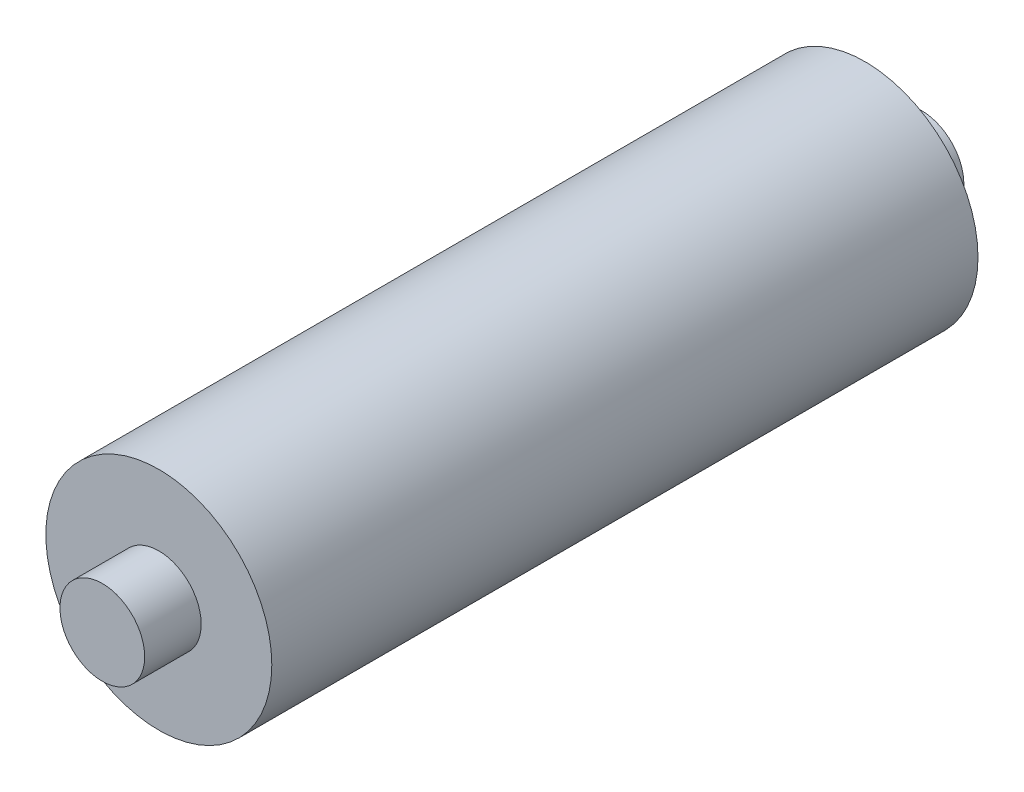
SolidWorks part; units mm, degrees
ref_plane "Front Plane" through (0, 0, 0) normal (0, 0, 1) x (1, 0, 0)
ref_plane "Top Plane" through (0, 0, 0) normal (0, 1, 0) x (1, 0, 0)
ref_plane "Right Plane" through (0, 0, 0) normal (1, 0, 0) x (0, 0, -1)
sketch "Sketch1" plane through (0, 0, 0) normal (0, 0, 1) x (1, 0, 0)
  circle A0 centre (0, 0) radius 40
  dimension "D1" = 80
extrude "Boss-Extrude1" add sketch "Sketch1" along normal blind 250
sketch "Sketch2" plane through (0, 0, 250) normal (0, 0, 1) x (1, 0, 0)
  circle A0 centre (0, 0) radius 15
  dimension "D1" = 30
extrude "Boss-Extrude2" add sketch "Sketch2" along normal blind 20
ref_plane "Plane1" through (0, 0, 125) normal (0, 0, 1) x (1, 0, 0)
mirror "Mirror1" about plane through (0, 0, 125) normal (0, 0, 1) of "Boss-Extrude2"
